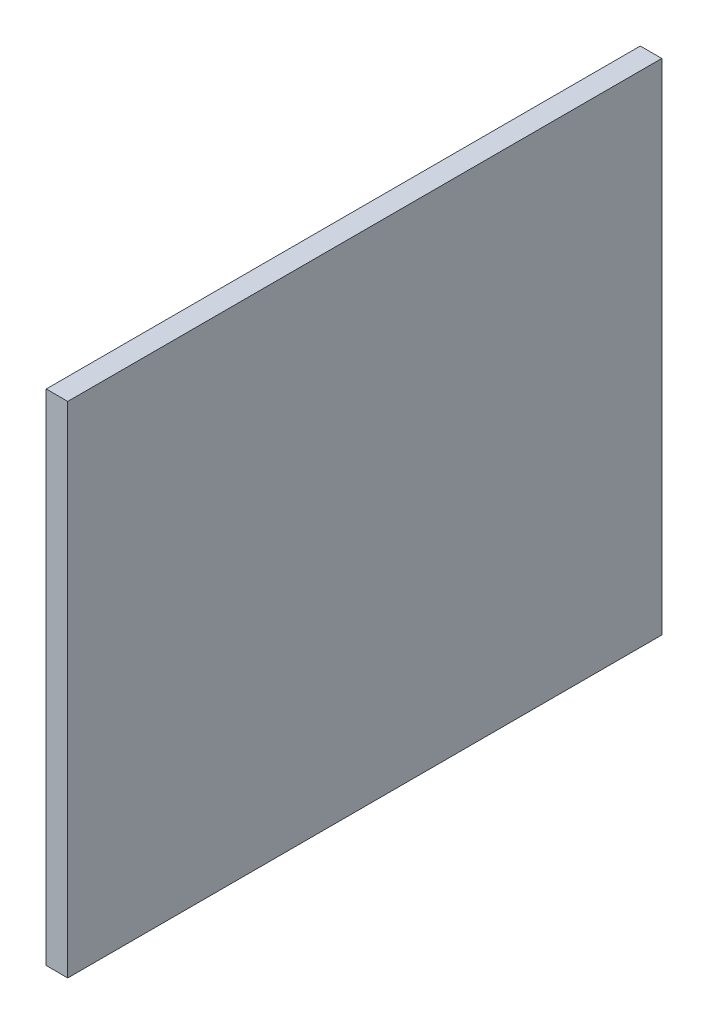
SolidWorks part; units mm, degrees
material "Alumina"
ref_plane "Front Plane" through (0, 0, 0) normal (0, 0, 1) x (1, 0, 0)
ref_plane "Top Plane" through (0, 0, 0) normal (0, 1, 0) x (1, 0, 0)
ref_plane "Right Plane" through (0, 0, 0) normal (1, 0, 0) x (0, 0, -1)
sketch "Sketch2" plane through (0, 0, 0) normal (1, 0, 0) x (0, 0, -1)
  line L1 (6.4336, -4.9109) -> (-7.3664, -4.9109)
  line L2 (6.4336, -4.9109) -> (6.4336, 6.6891)
  line L3 (6.4336, 6.6891) -> (-7.3664, 6.6891)
  line L4 (-7.3664, -4.9109) -> (-7.3664, 6.6891)
  dimension "D1" = 11.6
  dimension "D2" = 13.8
extrude "Boss-Extrude1" add sketch "Sketch2" along normal blind 0.5
